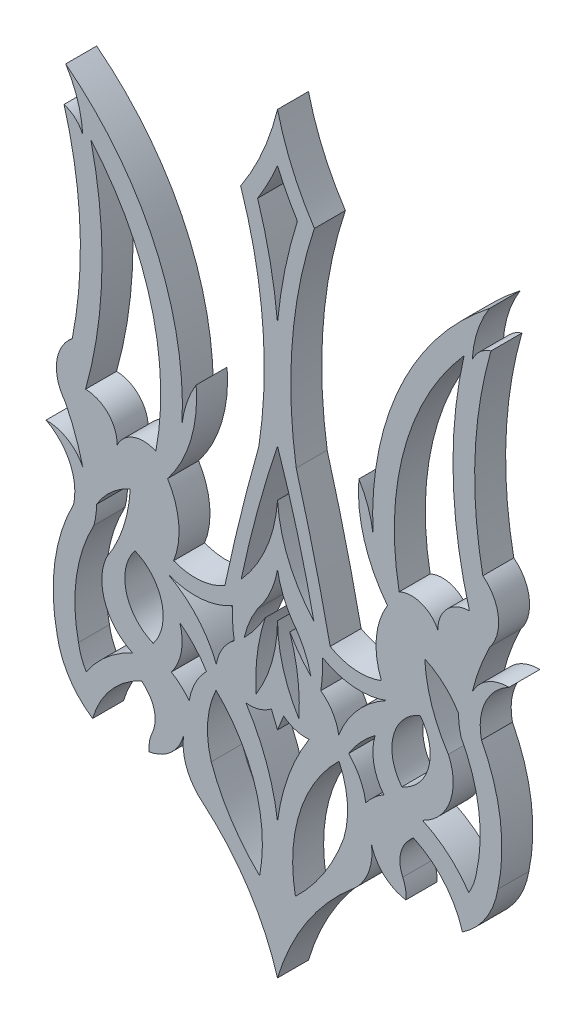
SolidWorks part; units mm, degrees
ref_plane "Спереди" through (0, 0, 0) normal (0, 0, 1) x (1, 0, 0)
ref_plane "Сверху" through (0, 0, 0) normal (0, 1, 0) x (1, 0, 0)
ref_plane "Справа" through (0, 0, 0) normal (1, 0, 0) x (0, 0, -1)
sketch "Эскиз1" [suppressed] plane through (0, 0, 0) normal (0, 0, 1) x (1, 0, 0)
  line L0 (87.6443, -23.7883) -> (87.6443, -6.8916) construction
  line L1 (87.6443, -6.8916) -> (87.6443, 352.3548) construction
  line L3 (87.6443, 68.6318) -> (85.6546, 73.5186)
  line L4 (87.6443, 68.6318) -> (89.6341, 73.5186)
  arc A0 (40.6207, 123.507) -> (44.6469, 97.5316) centre (120.5444, 122.5954) ccw
  arc A1 (40.6207, 123.507) -> (52.5559, 106.1421) centre (-51.0479, 47.7173) cw
  arc A2 (44.6469, 97.5316) -> (48.9353, 94.2011) centre (41.1464, 88.5981) cw
  arc A3 (48.9353, 94.2011) -> (48.9353, 107.9589) centre (131.9116, 101.08) cw
  arc A4 (52.5559, 106.1421) -> (53.1645, 101.095) centre (43.5258, 102.4931) cw
  arc A6 (53.1645, 101.095) -> (49.4634, 108.1691) centre (60.7326, 109.5597) cw
  arc A7 (48.935, 107.9555) -> (49.4634, 108.1691) centre (50.0675, 105.914) cw
  arc A8 (64.6822, 73.5186) -> (59.1188, 62.4923) centre (79.1678, 59.2931) ccw
  arc A9 (59.1188, 62.4923) -> (53.3348, 67.6488) centre (43.2754, 50.5432) ccw
  arc A10 (53.3348, 67.6488) -> (56.4809, 74.2644) centre (31.6379, 82.0231) ccw
  arc A11 (56.4809, 74.2644) -> (56.1084, 82.846) centre (34.8221, 77.623) ccw
  arc A12 (64.6822, 73.5186) -> (56.1084, 82.846) centre (35.8416, 55.6125) ccw
  arc A13 (41.6181, 95.7087) -> (47.5094, 72.7815) centre (35.854, 82.0071) cw
  arc A14 (41.6181, 95.7087) -> (47.5094, 72.7815) centre (53.0477, 86.4251) ccw
  arc A15 (25.6081, 56.3356) -> (38.7862, 66.0056) centre (60.8247, 22.1574) cw
  arc A16 (38.7862, 66.0056) -> (32.0434, 81.1637) centre (52.0503, 80.9846) cw
  arc A17 (40.0148, 95.7087) -> (32.0434, 81.1637) centre (52.4098, 79.4588) ccw
  arc A18 (40.0148, 95.7087) -> (34.589, 93.5264) centre (39.084, 90.1868) ccw
  arc A19 (41.6181, 98.1673) -> (34.1719, 94.2011) centre (40.4092, 91.464) ccw
  arc A20 (30.5806, 109.6374) -> (41.6181, 98.1673) centre (116.5629, 181.3309) ccw
  arc A21 (30.5806, 109.6374) -> (31.6379, 83.1978) centre (-35.2023, 93.7659) cw
  arc A22 (25.6081, 56.3356) -> (31.6379, 83.1978) centre (108.2418, 51.8945) cw
  arc A23 (34.1719, 94.2011) -> (34.589, 93.5264) centre (34.7179, 94.0723) ccw
  arc A24 (72.6436, 90.9214) -> (73.3927, 85.212) centre (115.3568, 93.6216) ccw
  arc A25 (70.0758, 80.9846) -> (73.3927, 85.212) centre (104.2196, 57.6099) cw
  arc A26 (70.0758, 80.9846) -> (60.9509, 89.3983) centre (44.0092, 61.8694) ccw
  arc A27 (60.9509, 89.3983) -> (72.6436, 90.9214) centre (64.518, 107.658) ccw
  arc A28 (80.7379, 32.2385) -> (67.7808, 69.8254) centre (31.257, 36.2081) ccw
  arc A29 (64.9288, 57.4953) -> (67.7808, 69.8254) centre (93.0087, 57.4953) cw
  arc A30 (80.7379, 32.2385) -> (64.9288, 57.4953) centre (119.8675, 74.307) cw
  arc A31 (94.5508, 32.2385) -> (110.3598, 57.4953) centre (55.4212, 74.307) ccw
  arc A32 (110.3598, 57.4953) -> (107.5079, 69.8254) centre (82.28, 57.4953) ccw
  arc A33 (94.5508, 32.2385) -> (107.5079, 69.8254) centre (144.0316, 36.2081) cw
  arc A34 (114.3378, 89.3983) -> (102.6451, 90.9214) centre (110.7707, 107.658) cw
  arc A35 (105.2129, 80.9846) -> (114.3378, 89.3983) centre (131.2795, 61.8694) cw
  arc A36 (105.2129, 80.9846) -> (101.896, 85.212) centre (71.069, 57.6099) ccw
  arc A37 (102.6451, 90.9214) -> (101.896, 85.212) centre (59.9318, 93.6216) cw
  arc A38 (141.1167, 94.2011) -> (140.6996, 93.5264) centre (140.5708, 94.0723) cw
  arc A39 (149.6806, 56.3356) -> (143.6508, 83.1978) centre (67.0469, 51.8945) ccw
  arc A40 (144.708, 109.6374) -> (143.6508, 83.1978) centre (210.491, 93.7659) ccw
  arc A41 (144.708, 109.6374) -> (133.6706, 98.1673) centre (58.7258, 181.3309) cw
  arc A42 (133.6706, 98.1673) -> (141.1167, 94.2011) centre (134.8795, 91.464) cw
  arc A43 (135.2739, 95.7087) -> (140.6996, 93.5264) centre (136.2047, 90.1868) cw
  arc A44 (135.2739, 95.7087) -> (143.2453, 81.1637) centre (122.8789, 79.4588) cw
  arc A45 (136.5025, 66.0056) -> (143.2453, 81.1637) centre (123.2384, 80.9846) ccw
  arc A46 (149.6806, 56.3356) -> (136.5025, 66.0056) centre (114.4639, 22.1574) ccw
  arc A47 (133.6706, 95.7087) -> (127.7793, 72.7815) centre (122.241, 86.4251) cw
  arc A48 (133.6706, 95.7087) -> (127.7793, 72.7815) centre (139.4347, 82.0071) ccw
  arc A49 (110.6065, 73.5186) -> (119.1803, 82.846) centre (139.4471, 55.6125) cw
  arc A50 (118.8077, 74.2644) -> (119.1803, 82.846) centre (140.4665, 77.623) cw
  arc A51 (121.9539, 67.6488) -> (118.8077, 74.2644) centre (143.6508, 82.0231) cw
  arc A52 (116.1699, 62.4923) -> (121.9539, 67.6488) centre (132.0132, 50.5432) cw
  arc A53 (110.6065, 73.5186) -> (116.1699, 62.4923) centre (96.1209, 59.2931) cw
  arc A54 (126.3537, 107.9555) -> (125.8253, 108.1691) centre (125.2211, 105.914) ccw
  arc A55 (122.1242, 101.095) -> (125.8253, 108.1691) centre (114.5561, 109.5597) ccw
  arc A56 (122.7327, 106.1421) -> (122.1242, 101.095) centre (131.7628, 102.4931) ccw
  arc A57 (126.3534, 94.2011) -> (126.3534, 107.9589) centre (43.3771, 101.08) ccw
  arc A58 (130.6418, 97.5316) -> (126.3534, 94.2011) centre (134.1423, 88.5981) ccw
  arc A59 (134.668, 123.507) -> (122.7327, 106.1421) centre (226.3366, 47.7173) ccw
  arc A60 (134.668, 123.507) -> (130.6418, 97.5316) centre (54.7443, 122.5954) cw
  arc A61 (75.9102, 104.8888) -> (87.6443, 132.8603) centre (41.1732, 135.9081) ccw
  arc A62 (75.9102, 104.8888) -> (87.6443, 148.0034) centre (451.7712, 25.7481) cw
  arc A63 (99.3785, 104.8888) -> (87.6443, 132.8603) centre (134.1154, 135.9081) cw
  arc A64 (99.3785, 104.8888) -> (87.6443, 148.0034) centre (-276.4825, 25.7481) ccw
  arc A65 (85.6546, 73.5186) -> (81.8714, 71.5335) centre (82.7705, 74.4176) cw
  arc A66 (87.6443, 53.083) -> (81.8714, 71.5335) centre (17.8027, 41.3588) ccw
  arc A67 (89.6341, 73.5186) -> (93.4173, 71.5335) centre (92.5182, 74.4176) ccw
  arc A68 (87.6443, 53.083) -> (93.4173, 71.5335) centre (157.486, 41.3588) cw
  arc A69 (87.6443, 111.5019) -> (75.9102, 93.6216) centre (57.0652, 118.7792) cw
  arc A70 (75.9102, 93.6216) -> (76.8685, 89.0118) centre (107.3806, 97.7594) ccw
  arc A71 (76.8685, 89.0118) -> (83.3447, 99.1087) centre (-45.6127, 174.6974) ccw
  arc A72 (83.3447, 99.1087) -> (78.1463, 84.8771) centre (62.4821, 98.6641) cw
  arc A73 (80.7379, 75.1856) -> (78.1463, 84.8771) centre (94.8769, 84.1588) cw
  arc A74 (80.7379, 75.1856) -> (83.7649, 75.1856) centre (82.2514, 76.6992) ccw
  arc A75 (83.7649, 75.1856) -> (82.2514, 83.8045) centre (69.0111, 77.037) ccw
  arc A76 (87.6443, 99.1626) -> (82.2514, 83.8045) centre (61.1079, 99.8548) cw
  arc A77 (91.5237, 75.1856) -> (93.0373, 83.8045) centre (106.2776, 77.037) cw
  arc A78 (94.5508, 75.1856) -> (91.5237, 75.1856) centre (93.0373, 76.6992) cw
  arc A79 (94.5508, 75.1856) -> (97.1424, 84.8771) centre (80.4118, 84.1588) ccw
  arc A80 (91.944, 99.1087) -> (97.1424, 84.8771) centre (112.8066, 98.6641) ccw
  arc A81 (98.4202, 89.0118) -> (91.944, 99.1087) centre (220.9014, 174.6974) cw
  arc A82 (99.3785, 93.6216) -> (98.4202, 89.0118) centre (67.908, 97.7594) cw
  arc A83 (87.6443, 111.5019) -> (99.3785, 93.6216) centre (118.2235, 118.7792) ccw
  arc A84 (87.6443, 99.1626) -> (93.0373, 83.8045) centre (114.1808, 99.8548) ccw
  spline S0 degree 3 poles (82.1027, 12.4657) (79.9341, 18.6914) (72.2067, 24.3569) (65.9185, 33.1059) (62.5505, 37.466) (60.1799, 39.943) (59.1555, 43.0897) (57.2647, 45.5543) (57.6286, 48.5225) (57.2368, 50.5201) (57.9183, 52.5735) (56.9495, 53.1909) (55.4861, 53.2614) (56.2486, 51.0634) (55.1896, 49.5498) (54.5036, 47.9051) (53.4075, 46.7279) (51.1035, 46.9894) (53.4402, 48.5489) (52.9045, 50.4248) (53.1315, 52.5819) (50.2686, 54.9996) (47.2077, 56.7477) (43.7411, 62.1873) (40.1307, 57.0478) (36.3563, 55.4003) (34.0123, 52.1175) (31.6232, 49.6208) (29.9193, 47.1505) (28.3136, 45.324) (28.3685, 43.599) (28.0916, 41.1132) (25.4838, 45.8805) (23.6707, 48.1541) (21.3506, 53.1893) (17.5941, 56.1294) (15.6148, 61.936) (15.5097, 68.0525) (15.9741, 74.6221) (17.289, 80.1758) (19.034, 85.376) (20.3139, 90.1381) (21.7721, 94.5747) (21.6409, 98.6721) (22.3333, 102.2806) (22.4635, 106.0403) (21.2552, 109.3896) (20.4336, 112.3281) (19.1765, 114.309) (17.3368, 115.252) (16.6151, 116.5408) (13.9501, 117.1637) (16.6597, 117.6233) (18.0151, 116.3143) (20.2861, 115.5733) (22.0029, 113.6892) (23.906, 112.8857) (24.7011, 110.1686) (25.9462, 111.2271) (24.8035, 113.2315) (24.159, 115.7716) (22.1122, 118.6068) (20.8946, 121.9867) (19.3322, 125.5441) (17.6129, 129.5089) (17.4458, 134.0046) (17.2957, 140.0912) (22.0505, 144.124) (21.6416, 148.9774) (21.7935, 153.6259) (21.4811, 159.1076) (22.6432, 165.8126) (23.1995, 173.1345) (24.6232, 181.9748) (23.765, 191.5281) (23.3918, 198.8905) (20.9362, 204.2846) (19.4503, 205.9635) (18.8575, 209.3893) (19.9586, 207.7428) (21.3919, 207.2624) (22.9247, 206.0347) (23.8774, 204.8209) (24.7322, 203.1653) (25.4143, 204.4362) (24.9731, 205.9617) (24.8711, 208.3515) (23.8043, 211.5847) (22.0026, 215.2682) (20.7759, 217.6358) (18.3336, 220.7887) (20.1657, 220.6691) (22.0637, 219.6809) (26.786, 216.3757) (31.4211, 210.9124) (35.9504, 205.2491) (38.6047, 200.7968) (41.0717, 196.8054) (43.4657, 192.4745) (45.5786, 187.3763) (48.797, 182.0166) (50.8485, 175.8116) (52.3971, 169.5049) (54.0904, 164.0713) (55.1853, 159.4561) (55.6944, 154.6896) (56.8351, 150.296) (56.4354, 145.8923) (56.5698, 142.4952) (56.7674, 140.6512) (56.6429, 138.4535) (58.4364, 140.4087) (58.5125, 143.2164) (59.7639, 147.3027) (59.1349, 150.6113) (60.546, 151.9302) (61.6062, 150.3802) (60.9783, 148.2843) (60.8195, 145.6095) (61.4206, 142.038) (60.3355, 138.7499) (59.3482, 135.2123) (57.8997, 132.2945) (56.5742, 128.4652) (54.2506, 125.5327) (53.3708, 122.086) (51.7176, 121.9147) (50.8205, 120.9474) (52.6711, 119.7166) (53.4663, 117.4305) (55.1877, 114.9802) (55.6358, 111.915) (55.4739, 109.1453) (55.6293, 106.276) (55.2189, 103.833) (54.3757, 101.9514) (54.0729, 100.4765) (53.8467, 98.7589) (56.0297, 98.8443) (57.6189, 98.1528) (59.6896, 98.0729) (61.8788, 98.0468) (64.294, 98.7043) (67.035, 98.9862) (69.132, 99.8917) (71.1395, 100.5472) (71.2883, 102.132) (71.3846, 103.98) (71.6843, 106.4326) (72.3165, 109.0602) (72.9684, 111.8403) (73.7279, 115.3959) (74.8536, 119.4926) (75.763, 123.5727) (76.9652, 127.2471) (78.2259, 131.0447) (79.3431, 135.0503) (80.7614, 142.4724) (83.4282, 150.1397) (82.9512, 158.3066) (84.0107, 163.2854) (83.59, 169.6597) (84.0559, 177.5749) (83.0482, 185.6995) (82.3476, 192.1007) (80.9886, 196.907) (79.5689, 201.5117) (78.8633, 206.1463) (77.0493, 209.8576) (76.689, 212.6324) (75.2575, 214.6117) (76.8358, 216.1245) (77.879, 218.2522) (80.4034, 220.257) (81.8163, 223.0476) (84.1194, 225.3097) (85.0477, 228.2799) (85.6117, 231.0457) (86.1825, 234.1961) (86.3896, 236.5507) (87.6443, 237.7908) knots 0 0 0 0 0.028658 0.043275 0.049534 0.054228 0.058819 0.064724 0.067657 0.072055 0.074743 0.075624 0.077091 0.080033 0.082665 0.085727 0.088171 0.089899 0.093085 0.09504 0.098738 0.10237 0.110881 0.116931 0.12534 0.130966 0.136851 0.143265 0.14693 0.150998 0.153453 0.155706 0.158836 0.169146 0.175056 0.182849 0.190745 0.202253 0.211081 0.2211 0.22852 0.236408 0.243941 0.249861 0.255135 0.260932 0.266943 0.271401 0.275062 0.277427 0.280411 0.282801 0.284651 0.288472 0.292184 0.295167 0.299832 0.302584 0.303471 0.305901 0.311305 0.31655 0.321491 0.327909 0.334558 0.341172 0.348631 0.361775 0.3653 0.370587 0.383408 0.390434 0.401952 0.417351 0.431602 0.445959 0.451733 0.457128 0.459446 0.461227 0.462918 0.467115 0.469213 0.471366 0.472356 0.474352 0.478803 0.483184 0.490226 0.496344 0.499774 0.500928 0.503188 0.510201 0.526825 0.536331 0.543637 0.550744 0.558021 0.566469 0.576206 0.586787 0.596488 0.606229 0.613083 0.618339 0.628411 0.633617 0.638971 0.643137 0.644483 0.645854 0.651354 0.659471 0.66475 0.665493 0.667175 0.670744 0.675956 0.67924 0.687368 0.691401 0.696251 0.702416 0.709709 0.714483 0.715763 0.717201 0.719145 0.723694 0.729034 0.732428 0.737794 0.741861 0.745654 0.749171 0.751124 0.753035 0.755611 0.758771 0.761604 0.764925 0.768896 0.773112 0.777417 0.779908 0.781699 0.784112 0.788713 0.792962 0.796626 0.8019 0.809759 0.816251 0.821199 0.827609 0.834746 0.840382 0.862553 0.871482 0.877812 0.8859 0.90082 0.914379 0.923643 0.930511 0.937411 0.945888 0.95211 0.95598 0.959297 0.961172 0.965011 0.970487 0.975505 0.979301 0.98517 0.98942 0.992411 1 1 1 1
  spline S1 degree 3 poles (82.1027, 12.4657) (84.2993, 11.04) (84.4898, 7.8171) (86.5127, 3.3725) (86.1614, 0.5556) (87.6443, -0.7518) knots 0 0 0 0 0.459955 0.640601 1 1 1 1
  spline S2 degree 3 poles (33.1492, 192.0361) (32.3239, 190.9776) (33.6073, 189.488) (33.8183, 187.2571) (33.5912, 184.1913) (34.768, 180.8287) (34.142, 177.3643) (34.7375, 174.2184) (33.416, 171.4352) (33.916, 167.4649) (33.6419, 163.6672) (32.426, 159.6409) (32.4019, 155.0102) (31.9063, 150.2145) (31.6211, 145.5238) (31.6773, 141.7351) (31.7172, 137.7233) (31.9002, 133.63) (32.978, 129.7883) (33.9667, 126.7415) (34.7739, 124.6373) (35.9477, 123.6027) (36.53, 122.8648) (37.5454, 121.5879) (37.4217, 123.1892) (37.5666, 124.6402) (37.3724, 126.6813) (37.8229, 128.5307) (36.0597, 129.5835) (35.484, 131.9144) (33.8251, 133.8023) (32.9988, 135.8671) (32.5775, 137.8995) (32.7484, 140.1683) (32.6969, 142.6647) (32.7204, 145.3503) (32.6794, 147.1018) (32.7472, 149.4742) (34.0356, 148.8725) (33.4484, 147.6005) (34.7834, 146.6454) (34.9602, 145.1083) (35.8397, 143.8377) (36.3762, 142.2481) (37.3299, 141.4461) (38.2688, 139.6692) (37.6169, 143.0252) (38.8152, 144.4393) (38.7035, 147.2313) (40.2653, 149.5487) (40.4515, 152.7002) (41.8549, 155.6423) (41.9859, 158.862) (43.852, 161.2171) (44.2768, 163.8863) (46.8497, 165.6494) (45.526, 168.176) (45.5393, 170.8684) (44.2898, 173.6945) (43.4083, 176.7928) (42.3605, 179.7494) (41.2587, 183.3179) (39.6884, 186.497) (37.9874, 189.0815) (37.1022, 190.9736) (35.9708, 192.4083) (35.546, 193.416) (34.9644, 194.6072) (34.481, 193.584) (35.0606, 192.9709) (35.4984, 191.9578) (36.1915, 190.5842) (37.1149, 188.6535) (38.6572, 186.6292) (39.1797, 184.1383) (40.3802, 181.9395) (40.9565, 179.5898) (41.4899, 177.0443) (41.4982, 174.3807) (41.5055, 171.851) (41.6679, 169.141) (41.2969, 167.7277) (41.5978, 165.5169) (40.8134, 166.0301) (40.5745, 166.8614) (40.5224, 168.2129) (40.2785, 170.2818) (39.5013, 172.7829) (39.3781, 175.9179) (37.6702, 178.7865) (37.4428, 182.0032) (36.3743, 184.7095) (35.2439, 187.1159) (34.7904, 189.6375) (33.4854, 190.5664) (33.1492, 192.0361) (32.3239, 190.9776) (33.6073, 189.488) knots -0.012612 -0.005761 -0.002075 0 0.007255 0.019718 0.029693 0.047672 0.065407 0.075398 0.089085 0.104151 0.127416 0.139155 0.159578 0.18822 0.203162 0.221786 0.238384 0.256378 0.275818 0.290943 0.298886 0.305592 0.309871 0.315048 0.316266 0.327773 0.336578 0.343481 0.349935 0.360303 0.374097 0.382594 0.389485 0.401439 0.412378 0.423035 0.435398 0.441227 0.444335 0.448491 0.455752 0.462248 0.468297 0.476116 0.48319 0.486816 0.495399 0.506278 0.515895 0.529177 0.542232 0.556628 0.571942 0.583258 0.594987 0.607033 0.616794 0.627412 0.64313 0.656674 0.670279 0.68463 0.706116 0.717022 0.725407 0.734132 0.739585 0.743026 0.745433 0.749878 0.753371 0.760138 0.77021 0.781747 0.793286 0.803307 0.814728 0.82514 0.837744 0.849666 0.859355 0.871506 0.875734 0.877718 0.88086 0.887378 0.895398 0.908474 0.921918 0.936196 0.951395 0.963938 0.974273 0.987388 0.994239 0.997925 1 1.007255 1.019718 1.029693 only from (32.7088, 191.4049) to (32.7088, 191.4049)
  spline S3 degree 3 poles (47.2686, 158.0754) (47.7213, 162.9241) (45.2966, 161.2742) (45.964, 159.5651) (45.3251, 157.6959) (44.4757, 155.1989) (43.5549, 151.8687) (42.7549, 147.538) (42.2447, 143.4146) (41.541, 139.9722) (41.6157, 137.7124) (41.6536, 136.1284) (41.4943, 134.633) (42.3593, 133.2272) (43.8596, 131.8548) (45.2388, 130.3901) (46.1674, 128.8242) (47.1879, 127.4737) (48.047, 126.2665) (49.7786, 126.1221) (49.3203, 127.9742) (49.5218, 129.7723) (49.5314, 132.9689) (49.4172, 136.5451) (49.5613, 140.5116) (49.4214, 144.4013) (48.898, 148.034) (48.8314, 151.5082) (48.2414, 155.3338) (47.2686, 158.0754) (47.7213, 162.9241) (45.2966, 161.2742) knots -0.143996 -0.098331 -0.035995 0 0.019516 0.041316 0.063925 0.095286 0.145724 0.199179 0.268238 0.309127 0.336564 0.356607 0.371756 0.394271 0.417403 0.452475 0.472504 0.488578 0.519641 0.527249 0.545927 0.569891 0.608527 0.666292 0.712585 0.763868 0.81928 0.856004 0.901669 0.964005 1 1.019516 1.041316 1.063925 only from (46.9629, 162.1437) to (46.9629, 162.1437)
  spline S4 degree 3 poles (128.0201, 158.0754) (127.5674, 162.9241) (129.9921, 161.2742) (129.3247, 159.5651) (129.9636, 157.6959) (130.813, 155.1989) (131.7338, 151.8687) (132.5337, 147.538) (133.044, 143.4146) (133.7477, 139.9722) (133.673, 137.7124) (133.6351, 136.1284) (133.7944, 134.633) (132.9293, 133.2272) (131.4291, 131.8548) (130.0499, 130.3901) (129.1213, 128.8242) (128.1008, 127.4737) (127.2417, 126.2665) (125.5101, 126.1221) (125.9684, 127.9742) (125.7669, 129.7723) (125.7573, 132.9689) (125.8715, 136.5451) (125.7274, 140.5116) (125.8672, 144.4013) (126.3907, 148.034) (126.4573, 151.5082) (127.0473, 155.3338) (128.0201, 158.0754) (127.5674, 162.9241) (129.9921, 161.2742) knots -0.143996 -0.098331 -0.035995 0 0.019516 0.041316 0.063925 0.095286 0.145724 0.199179 0.268238 0.309127 0.336564 0.356607 0.371756 0.394271 0.417403 0.452475 0.472504 0.488578 0.519641 0.527249 0.545927 0.569891 0.608527 0.666292 0.712585 0.763868 0.81928 0.856004 0.901669 0.964005 1 1.019516 1.041316 1.063925 only from (128.3258, 162.1437) to (128.3258, 162.1437)
  spline S5 degree 3 poles (142.1395, 192.0361) (142.9648, 190.9776) (141.6814, 189.488) (141.4704, 187.2571) (141.6974, 184.1913) (140.5207, 180.8287) (141.1466, 177.3643) (140.5512, 174.2184) (141.8727, 171.4352) (141.3727, 167.4649) (141.6467, 163.6672) (142.8627, 159.6409) (142.8867, 155.0102) (143.3824, 150.2145) (143.6676, 145.5238) (143.6114, 141.7351) (143.5715, 137.7233) (143.3884, 133.63) (142.3107, 129.7883) (141.322, 126.7415) (140.5148, 124.6373) (139.341, 123.6027) (138.7587, 122.8648) (137.7433, 121.5879) (137.867, 123.1892) (137.7221, 124.6402) (137.9163, 126.6813) (137.4658, 128.5307) (139.229, 129.5835) (139.8047, 131.9144) (141.4636, 133.8023) (142.2899, 135.8671) (142.7112, 137.8995) (142.5403, 140.1683) (142.5918, 142.6647) (142.5683, 145.3503) (142.6093, 147.1018) (142.5414, 149.4742) (141.2531, 148.8725) (141.8402, 147.6005) (140.5053, 146.6454) (140.3285, 145.1083) (139.4489, 143.8377) (138.9125, 142.2481) (137.9587, 141.4461) (137.0198, 139.6692) (137.6717, 143.0252) (136.4735, 144.4393) (136.5852, 147.2313) (135.0234, 149.5487) (134.8372, 152.7002) (133.4338, 155.6423) (133.3028, 158.862) (131.4366, 161.2171) (131.0119, 163.8863) (128.439, 165.6494) (129.7627, 168.176) (129.7494, 170.8684) (130.9989, 173.6945) (131.8804, 176.7928) (132.9282, 179.7494) (134.0299, 183.3179) (135.6003, 186.497) (137.3012, 189.0815) (138.1865, 190.9736) (139.3179, 192.4083) (139.7427, 193.416) (140.3243, 194.6072) (140.8077, 193.584) (140.2281, 192.9709) (139.7902, 191.9578) (139.0971, 190.5842) (138.1737, 188.6535) (136.6315, 186.6292) (136.109, 184.1383) (134.9085, 181.9395) (134.3322, 179.5898) (133.7988, 177.0443) (133.7905, 174.3807) (133.7832, 171.851) (133.6208, 169.141) (133.9918, 167.7277) (133.6909, 165.5169) (134.4753, 166.0301) (134.7142, 166.8614) (134.7663, 168.2129) (135.0101, 170.2818) (135.7874, 172.7829) (135.9106, 175.9179) (137.6185, 178.7865) (137.8459, 182.0032) (138.9144, 184.7095) (140.0448, 187.1159) (140.4983, 189.6375) (141.8033, 190.5664) (142.1395, 192.0361) (142.9648, 190.9776) (141.6814, 189.488) knots -0.012612 -0.005761 -0.002075 0 0.007255 0.019718 0.029693 0.047672 0.065407 0.075398 0.089085 0.104151 0.127416 0.139155 0.159578 0.18822 0.203162 0.221786 0.238384 0.256378 0.275818 0.290943 0.298886 0.305592 0.309871 0.315048 0.316266 0.327773 0.336578 0.343481 0.349935 0.360303 0.374097 0.382594 0.389485 0.401439 0.412378 0.423035 0.435398 0.441227 0.444335 0.448491 0.455752 0.462248 0.468297 0.476116 0.48319 0.486816 0.495399 0.506278 0.515895 0.529177 0.542232 0.556628 0.571942 0.583258 0.594987 0.607033 0.616794 0.627412 0.64313 0.656674 0.670279 0.68463 0.706116 0.717022 0.725407 0.734132 0.739585 0.743026 0.745433 0.749878 0.753371 0.760138 0.77021 0.781747 0.793286 0.803307 0.814728 0.82514 0.837744 0.849666 0.859355 0.871506 0.875734 0.877718 0.88086 0.887378 0.895398 0.908474 0.921918 0.936196 0.951395 0.963938 0.974273 0.987388 0.994239 0.997925 1 1.007255 1.019718 1.029693 only from (142.5799, 191.4049) to (142.5799, 191.4049)
  spline S6 degree 3 poles (93.186, 12.4657) (90.9894, 11.04) (90.7989, 7.8171) (88.776, 3.3725) (89.1273, 0.5556) (87.6443, -0.7518) knots 0 0 0 0 0.459955 0.640601 1 1 1 1
  spline S7 degree 3 poles (93.186, 12.4657) (95.3546, 18.6914) (103.082, 24.3569) (109.3702, 33.1059) (112.7382, 37.466) (115.1088, 39.943) (116.1332, 43.0897) (118.024, 45.5543) (117.6601, 48.5225) (118.0519, 50.5201) (117.3704, 52.5735) (118.3392, 53.1909) (119.8025, 53.2614) (119.0401, 51.0634) (120.0991, 49.5498) (120.7851, 47.9051) (121.8812, 46.7279) (124.1852, 46.9894) (121.8484, 48.5489) (122.3841, 50.4248) (122.1572, 52.5819) (125.02, 54.9996) (128.081, 56.7477) (131.5476, 62.1873) (135.158, 57.0478) (138.9324, 55.4003) (141.2764, 52.1175) (143.6655, 49.6208) (145.3694, 47.1505) (146.9751, 45.324) (146.9202, 43.599) (147.197, 41.1132) (149.8049, 45.8805) (151.618, 48.1541) (153.9381, 53.1893) (157.6945, 56.1294) (159.6739, 61.936) (159.779, 68.0525) (159.3146, 74.6221) (157.9997, 80.1758) (156.2547, 85.376) (154.9747, 90.1381) (153.5166, 94.5747) (153.6478, 98.6721) (152.9553, 102.2806) (152.8252, 106.0403) (154.0334, 109.3896) (154.8551, 112.3281) (156.1122, 114.309) (157.9519, 115.252) (158.6736, 116.5408) (161.3386, 117.1637) (158.629, 117.6233) (157.2736, 116.3143) (155.0026, 115.5733) (153.2858, 113.6892) (151.3827, 112.8857) (150.5876, 110.1686) (149.3425, 111.2271) (150.4852, 113.2315) (151.1297, 115.7716) (153.1765, 118.6068) (154.3941, 121.9867) (155.9564, 125.5441) (157.6757, 129.5089) (157.8429, 134.0046) (157.993, 140.0912) (153.2382, 144.124) (153.6471, 148.9774) (153.4952, 153.6259) (153.8076, 159.1076) (152.6455, 165.8126) (152.0892, 173.1345) (150.6655, 181.9748) (151.5237, 191.5281) (151.8969, 198.8905) (154.3525, 204.2846) (155.8384, 205.9635) (156.4312, 209.3893) (155.33, 207.7428) (153.8968, 207.2624) (152.364, 206.0347) (151.4112, 204.8209) (150.5565, 203.1653) (149.8744, 204.4362) (150.3156, 205.9617) (150.4175, 208.3515) (151.4844, 211.5847) (153.2861, 215.2682) (154.5127, 217.6358) (156.9551, 220.7887) (155.1229, 220.6691) (153.225, 219.6809) (148.5027, 216.3757) (143.8676, 210.9124) (139.3383, 205.2491) (136.684, 200.7968) (134.217, 196.8054) (131.823, 192.4745) (129.7101, 187.3763) (126.4917, 182.0166) (124.4402, 175.8116) (122.8915, 169.5049) (121.1983, 164.0713) (120.1034, 159.4561) (119.5943, 154.6896) (118.4535, 150.296) (118.8533, 145.8923) (118.7188, 142.4952) (118.5213, 140.6512) (118.6458, 138.4535) (116.8523, 140.4087) (116.7762, 143.2164) (115.5248, 147.3027) (116.1538, 150.6113) (114.7427, 151.9302) (113.6825, 150.3802) (114.3104, 148.2843) (114.4692, 145.6095) (113.8681, 142.038) (114.9532, 138.7499) (115.9405, 135.2123) (117.389, 132.2945) (118.7145, 128.4652) (121.0381, 125.5327) (121.9179, 122.086) (123.5711, 121.9147) (124.4682, 120.9474) (122.6176, 119.7166) (121.8223, 117.4305) (120.101, 114.9802) (119.6529, 111.915) (119.8148, 109.1453) (119.6594, 106.276) (120.0698, 103.833) (120.913, 101.9514) (121.2157, 100.4765) (121.442, 98.7589) (119.259, 98.8443) (117.6698, 98.1528) (115.5991, 98.0729) (113.4099, 98.0468) (110.9947, 98.7043) (108.2537, 98.9862) (106.1566, 99.8917) (104.1492, 100.5472) (104.0003, 102.132) (103.9041, 103.98) (103.6044, 106.4326) (102.9722, 109.0602) (102.3203, 111.8403) (101.5608, 115.3959) (100.435, 119.4926) (99.5257, 123.5727) (98.3234, 127.2471) (97.0628, 131.0447) (95.9456, 135.0503) (94.5272, 142.4724) (91.8605, 150.1397) (92.3375, 158.3066) (91.278, 163.2854) (91.6987, 169.6597) (91.2328, 177.5749) (92.2405, 185.6995) (92.9411, 192.1007) (94.3001, 196.907) (95.7197, 201.5117) (96.4254, 206.1463) (98.2393, 209.8576) (98.5997, 212.6324) (100.0312, 214.6117) (98.4528, 216.1245) (97.4097, 218.2522) (94.8853, 220.257) (93.4724, 223.0476) (91.1693, 225.3097) (90.2409, 228.2799) (89.677, 231.0457) (89.1062, 234.1961) (88.8991, 236.5507) (87.6443, 237.7908) knots 0 0 0 0 0.028658 0.043275 0.049534 0.054228 0.058819 0.064724 0.067657 0.072055 0.074743 0.075624 0.077091 0.080033 0.082665 0.085727 0.088171 0.089899 0.093085 0.09504 0.098738 0.10237 0.110881 0.116931 0.12534 0.130966 0.136851 0.143265 0.14693 0.150998 0.153453 0.155706 0.158836 0.169146 0.175056 0.182849 0.190745 0.202253 0.211081 0.2211 0.22852 0.236408 0.243941 0.249861 0.255135 0.260932 0.266943 0.271401 0.275062 0.277427 0.280411 0.282801 0.284651 0.288472 0.292184 0.295167 0.299832 0.302584 0.303471 0.305901 0.311305 0.31655 0.321491 0.327909 0.334558 0.341172 0.348631 0.361775 0.3653 0.370587 0.383408 0.390434 0.401952 0.417351 0.431602 0.445959 0.451733 0.457128 0.459446 0.461227 0.462918 0.467115 0.469213 0.471366 0.472356 0.474352 0.478803 0.483184 0.490226 0.496344 0.499774 0.500928 0.503188 0.510201 0.526825 0.536331 0.543637 0.550744 0.558021 0.566469 0.576206 0.586787 0.596488 0.606229 0.613083 0.618339 0.628411 0.633617 0.638971 0.643137 0.644483 0.645854 0.651354 0.659471 0.66475 0.665493 0.667175 0.670744 0.675956 0.67924 0.687368 0.691401 0.696251 0.702416 0.709709 0.714483 0.715763 0.717201 0.719145 0.723694 0.729034 0.732428 0.737794 0.741861 0.745654 0.749171 0.751124 0.753035 0.755611 0.758771 0.761604 0.764925 0.768896 0.773112 0.777417 0.779908 0.781699 0.784112 0.788713 0.792962 0.796626 0.8019 0.809759 0.816251 0.821199 0.827609 0.834746 0.840382 0.862553 0.871482 0.877812 0.8859 0.90082 0.914379 0.923643 0.930511 0.937411 0.945888 0.95211 0.95598 0.959297 0.961172 0.965011 0.970487 0.975505 0.979301 0.98517 0.98942 0.992411 1 1 1 1
sketch "Эскиз3" plane through (0, 0, 0) normal (0, 0, 1) x (1, 0, 0)
  line L0 (87.6443, -0.7518) -> (87.6443, -30.7439) construction
  line L1 (75.7373, 214.8271) -> (99.5514, 214.8271) construction
  line L2 (87.6443, 214.8271) -> (87.6443, 245.1652) construction
  arc A0 (75.7373, 214.8271) -> (87.6443, 242.1865) centre (3.1746, 262.6778) ccw
  arc A2 (75.7373, 214.8271) -> (81.6055, 144.874) centre (-65.9765, 167.7164) cw
  arc A3 (81.6055, 144.874) -> (70.6377, 100.4834) centre (729.5469, -38.7656) ccw
  arc A4 (70.6377, 100.4834) -> (54.1195, 99.18) centre (61.0278, 116.9518) cw
  arc A5 (54.1195, 99.18) -> (52.147, 121.1645) centre (31.2493, 108.2088) ccw
  arc A6 (52.147, 121.1645) -> (61.3729, 151.9663) centre (17.0866, 148.4485) ccw
  arc A7 (61.3729, 151.9663) -> (56.8067, 138.8308) centre (89.4398, 134.8482) ccw
  arc A8 (56.8067, 138.8308) -> (19.2332, 220.6949) centre (-40.5564, 143.6983) ccw
  arc A9 (19.2332, 220.6949) -> (24.7593, 203.6092) centre (-10.9905, 201.483) cw
  arc A10 (24.7593, 203.6092) -> (18.7084, 209.1008) centre (15.8046, 199.8218) ccw
  arc A11 (18.7084, 209.1008) -> (21.3399, 144.8893) centre (-112.1058, 171.5801) cw
  arc A12 (21.3399, 144.8893) -> (19.102, 126.0824) centre (29.6244, 134.3669) ccw
  arc A13 (19.102, 126.0824) -> (24.7805, 110.6673) centre (-47.0296, 92.9675) cw
  arc A14 (24.7805, 110.6673) -> (12.8982, 117.9136) centre (13.0914, 104.8649) ccw
  arc A15 (12.8982, 117.9136) -> (21.781, 98.7337) centre (4.7748, 102.5045) cw
  arc A16 (21.781, 98.7337) -> (16.4854, 59.6475) centre (73.3534, 71.8446) ccw
  arc A17 (16.4854, 59.6475) -> (27.9301, 41.9549) centre (42.5937, 63.9882) ccw
  arc A18 (27.9301, 41.9549) -> (43.7562, 60.4021) centre (55.9548, 33.9245) cw
  arc A19 (43.7562, 60.4021) -> (46.0707, 57.9309) centre (32.5904, 47.6247) cw
  arc A20 (47.2033, 47.6608) -> (46.2055, 41.7904) centre (57.5332, 42.885) ccw
  arc A21 (46.2055, 41.7904) -> (57.3048, 51.8905) centre (44.028, 55.3321) ccw
  arc A22 (57.3048, 51.8905) -> (63.4952, 36.2204) centre (74.3192, 49.5541) ccw
  arc A23 (63.4952, 36.2204) -> (87.6443, -0.7518) centre (13.2717, -22.957) cw
  arc A24 (111.7935, 36.2204) -> (87.6443, -0.7518) centre (162.017, -22.957) ccw
  arc A25 (117.9838, 51.8905) -> (111.7935, 36.2204) centre (100.9695, 49.5541) cw
  arc A26 (129.0831, 41.7904) -> (117.9838, 51.8905) centre (131.2607, 55.3321) cw
  arc A27 (128.0854, 47.6608) -> (129.0831, 41.7904) centre (117.7555, 42.885) cw
  arc A28 (131.5325, 60.4021) -> (129.218, 57.9309) centre (142.6983, 47.6247) ccw
  arc A29 (147.3585, 41.9549) -> (131.5325, 60.4021) centre (119.3338, 33.9245) ccw
  arc A30 (158.8033, 59.6475) -> (147.3585, 41.9549) centre (132.695, 63.9882) cw
  arc A31 (153.5077, 98.7337) -> (158.8033, 59.6475) centre (101.9353, 71.8446) cw
  arc A32 (162.3905, 117.9136) -> (153.5077, 98.7337) centre (170.5139, 102.5045) ccw
  arc A33 (150.5081, 110.6673) -> (162.3905, 117.9136) centre (162.1973, 104.8649) cw
  arc A34 (156.1867, 126.0824) -> (150.5081, 110.6673) centre (222.3183, 92.9675) ccw
  arc A35 (153.9488, 144.8893) -> (156.1867, 126.0824) centre (145.6643, 134.3669) cw
  arc A36 (156.5803, 209.1008) -> (153.9488, 144.8893) centre (287.3945, 171.5801) ccw
  arc A37 (150.5293, 203.6092) -> (156.5803, 209.1008) centre (159.4841, 199.8218) cw
  arc A38 (156.0554, 220.6949) -> (150.5293, 203.6092) centre (186.2792, 201.483) ccw
  arc A39 (118.482, 138.8308) -> (156.0554, 220.6949) centre (215.8451, 143.6983) cw
  arc A40 (113.9158, 151.9663) -> (118.482, 138.8308) centre (85.8489, 134.8482) cw
  arc A41 (123.1417, 121.1645) -> (113.9158, 151.9663) centre (158.202, 148.4485) cw
  arc A42 (121.1692, 99.18) -> (123.1417, 121.1645) centre (144.0394, 108.2088) cw
  arc A43 (104.651, 100.4834) -> (121.1692, 99.18) centre (114.2609, 116.9518) ccw
  arc A44 (93.6832, 144.874) -> (104.651, 100.4834) centre (-554.2582, -38.7656) cw
  arc A45 (99.5514, 214.8271) -> (93.6832, 144.874) centre (241.2652, 167.7164) ccw
  arc A47 (99.5514, 214.8271) -> (87.6443, 242.1865) centre (172.1141, 262.6778) cw
  arc A48 (46.0707, 57.9309) -> (47.2033, 47.6608) centre (38.1265, 51.8573) cw
  arc A49 (129.218, 57.9309) -> (128.0854, 47.6608) centre (137.1622, 51.8573) ccw
  point P110 (49.2752, 50.7157)
  point P113 (126.0135, 50.7157)
  dimension "D1" = 10
  dimension "D2" = 10
extrude "Бобышка-Вытянуть1" add sketch "Эскиз3" along normal blind 10
sketch "Эскиз4" plane through (0, 0, 0) normal (0, 0, 1) x (1, 0, 0)
  line L0 (87.6443, -0.7518) -> (87.6443, -32.3218) construction
  line L1 (85.6546, 73.5186) -> (87.6443, 68.6318)
  line L2 (87.6443, 68.6318) -> (89.6341, 73.5186)
  arc A0 (87.6443, 148.0034) -> (75.9102, 104.8888) centre (451.7712, 25.7481) ccw
  arc A1 (87.6443, 132.8603) -> (75.9102, 104.8888) centre (41.1732, 135.9081) cw
  arc A2 (67.7808, 69.8254) -> (81.8714, 24.9568) centre (33.1175, 34.2929) cw
  arc A3 (81.8714, 24.9568) -> (66.2431, 49.0031) centre (124.8767, 70.0089) cw
  arc A4 (66.2431, 49.0031) -> (67.7808, 69.8254) centre (94.1751, 57.4083) cw
  arc A5 (87.6443, 42.9742) -> (77.4425, 71.0893) centre (20.2867, 34.4413) ccw
  arc A7 (64.6822, 73.5186) -> (56.1084, 82.846) centre (35.8416, 55.6125) ccw
  arc A8 (64.6822, 73.5186) -> (59.1188, 62.4923) centre (79.1678, 59.2931) ccw
  arc A9 (53.3348, 67.6488) -> (56.1084, 82.846) centre (40.0944, 77.917) ccw
  arc A10 (59.1188, 62.4923) -> (53.3348, 67.6488) centre (43.2754, 50.5432) ccw
  arc A12 (67.908, 77.0685) -> (52.3079, 94.5198) centre (36.5563, 64.7406) ccw
  arc A13 (67.908, 77.0685) -> (73.672, 86.5781) centre (82.0844, 74.9775) cw
  arc A14 (73.672, 86.5781) -> (73.1577, 96.1649) centre (115.3568, 93.6216) cw
  arc A15 (41.6181, 95.7087) -> (47.5094, 72.7815) centre (35.854, 82.0071) cw
  arc A16 (41.6181, 95.7087) -> (47.5094, 72.7815) centre (53.0477, 86.4251) ccw
  arc A17 (87.6443, 113.4827) -> (81.1136, 99.1626) centre (57.0652, 118.7792) cw
  arc A18 (81.1136, 99.1626) -> (76.8685, 89.0118) centre (107.8316, 82.0261) ccw
  arc A19 (76.8685, 89.0118) -> (83.6747, 98.0262) centre (42.0362, 122.3882) ccw
  arc A20 (83.6747, 98.0262) -> (80.7379, 75.1856) centre (141.0886, 79.0348) ccw
  arc A21 (80.7379, 75.1856) -> (87.6443, 99.1626) centre (41.3033, 99.5278) ccw
  arc A22 (94.5508, 75.1856) -> (87.6443, 99.1626) centre (133.9853, 99.5278) cw
  arc A23 (91.614, 98.0262) -> (94.5508, 75.1856) centre (34.2001, 79.0348) cw
  arc A24 (98.4202, 89.0118) -> (91.614, 98.0262) centre (133.2525, 122.3882) cw
  arc A25 (94.1751, 99.1626) -> (98.4202, 89.0118) centre (67.4571, 82.0261) cw
  arc A26 (87.6443, 113.4827) -> (94.1751, 99.1626) centre (118.2235, 118.7792) ccw
  arc A27 (133.6706, 95.7087) -> (127.7793, 72.7815) centre (122.241, 86.4251) cw
  arc A28 (133.6706, 95.7087) -> (127.7793, 72.7815) centre (139.4347, 82.0071) ccw
  arc A29 (101.6166, 86.5781) -> (102.131, 96.1649) centre (59.9318, 93.6216) ccw
  arc A30 (107.3806, 77.0685) -> (101.6166, 86.5781) centre (93.2043, 74.9775) ccw
  arc A31 (107.3806, 77.0685) -> (122.9808, 94.5198) centre (138.7324, 64.7406) cw
  arc A33 (116.1699, 62.4923) -> (121.9539, 67.6488) centre (132.0132, 50.5432) cw
  arc A34 (121.9539, 67.6488) -> (119.1803, 82.846) centre (135.1943, 77.917) cw
  arc A35 (110.6065, 73.5186) -> (116.1699, 62.4923) centre (96.1209, 59.2931) cw
  arc A36 (110.6065, 73.5186) -> (119.1803, 82.846) centre (139.4471, 55.6125) cw
  arc A38 (87.6443, 42.9742) -> (97.8462, 71.0893) centre (155.002, 34.4413) cw
  arc A39 (109.0456, 49.0031) -> (107.5079, 69.8254) centre (81.1136, 57.4083) ccw
  arc A40 (93.4173, 24.9568) -> (109.0456, 49.0031) centre (50.412, 70.0089) ccw
  arc A41 (107.5079, 69.8254) -> (93.4173, 24.9568) centre (142.1712, 34.2929) ccw
  arc A42 (87.6443, 132.8603) -> (99.3785, 104.8888) centre (134.1154, 135.9081) ccw
  arc A43 (87.6443, 148.0034) -> (99.3785, 104.8888) centre (-276.4825, 25.7481) cw
  arc A44 (77.4425, 71.0893) -> (85.6546, 73.5186) centre (78.6188, 82.2081) ccw
  arc A45 (97.8462, 71.0893) -> (89.6341, 73.5186) centre (96.6699, 82.2081) cw
  arc A71 (40.8271, 66.7598) -> (32.4731, 89.3983) centre (47.9693, 82.256) cw
  arc A72 (32.4731, 89.3983) -> (40.0944, 112.2971) centre (-5.435, 114.7328) ccw
  arc A73 (40.0944, 112.2971) -> (29.194, 102.5045) centre (50.3212, 89.9502) ccw
  arc A75 (28.3709, 96.2178) -> (16.1626, 124.1058) centre (4.7748, 102.5045) ccw
  arc A76 (23.3657, 60.9491) -> (25.8866, 53.997) centre (42.5937, 63.9882) ccw
  arc A77 (28.3709, 96.2178) -> (23.3657, 60.9491) centre (73.3534, 71.8446) ccw
  arc A78 (40.8271, 66.7598) -> (25.8866, 53.997) centre (55.9548, 33.9245) ccw
  arc A79 (28.3709, 96.2178) -> (29.194, 102.5045) centre (4.7748, 102.5045) ccw
  arc A80 (23.3657, 60.9491) -> (25.8866, 53.997) centre (42.5937, 63.9882) ccw
  arc A81 (28.3709, 96.2178) -> (23.3657, 60.9491) centre (73.3534, 71.8446) ccw
  arc A82 (40.8271, 66.7598) -> (25.8866, 53.997) centre (55.9548, 33.9245) ccw
  arc A266 (49.8154, 139.1803) -> (14.94, 215.166) centre (-40.5564, 143.6983) ccw
  arc A267 (48.3554, 126.9004) -> (27.3869, 203.4577) centre (-40.5564, 143.6983) ccw
  arc A268 (25.6623, 132.9232) -> (35.854, 122.3882) centre (25.4906, 122.5599) cw
  arc A269 (28.204, 143.5164) -> (25.4371, 211.0307) centre (-112.1058, 171.5801) ccw
  arc A270 (25.6623, 132.9232) -> (27.3869, 203.4577) centre (-112.1058, 171.5801) ccw
  arc A271 (35.854, 122.3882) -> (48.3554, 126.9004) centre (44.3608, 118.3936) cw
  arc A272 (151.923, 60.9491) -> (149.4021, 53.997) centre (132.695, 63.9882) cw
  arc A273 (134.4616, 66.7598) -> (149.4021, 53.997) centre (119.3338, 33.9245) cw
  arc A274 (134.4616, 66.7598) -> (142.8156, 89.3983) centre (127.3193, 82.256) ccw
  arc A275 (146.9178, 96.2178) -> (151.923, 60.9491) centre (101.9353, 71.8446) cw
  arc A276 (146.9178, 96.2178) -> (146.0947, 102.5045) centre (170.5139, 102.5045) cw
  arc A277 (135.1943, 112.2971) -> (146.0947, 102.5045) centre (124.9674, 89.9502) cw
  arc A278 (142.8156, 89.3983) -> (135.1943, 112.2971) centre (180.7237, 114.7328) cw
  arc A279 (139.4347, 122.3882) -> (126.9333, 126.9004) centre (130.9279, 118.3936) ccw
  arc A280 (149.6264, 132.9232) -> (139.4347, 122.3882) centre (149.798, 122.5599) ccw
  arc A281 (149.6264, 132.9232) -> (147.9018, 203.4577) centre (287.3945, 171.5801) cw
  arc A282 (126.9333, 126.9004) -> (147.9018, 203.4577) centre (215.8451, 143.6983) cw
  arc A322 (94.0669, 214.1199) -> (88.742, 144.1093) centre (241.2652, 167.7164) ccw
  arc A323 (82.7853, 241.0077) -> (94.0669, 214.1199) centre (172.1141, 262.6778) ccw
  arc A324 (94.0669, 214.1199) -> (87.6443, 182.5908) centre (241.2652, 167.7164) ccw
  arc A325 (87.6443, 226.4274) -> (94.0669, 214.1199) centre (172.1141, 262.6778) ccw
  arc A328 (122.9808, 94.5198) -> (102.131, 96.1649) centre (114.2609, 116.9518) cw
  arc A329 (86.5466, 144.1093) -> (81.2218, 214.1199) centre (-65.9765, 167.7164) ccw
  arc A330 (81.2218, 214.1199) -> (92.5034, 241.0077) centre (3.1746, 262.6778) ccw
  arc A331 (87.6443, 182.5908) -> (81.2218, 214.1199) centre (-65.9765, 167.7164) ccw
  arc A332 (81.2218, 214.1199) -> (87.6443, 226.4274) centre (3.1746, 262.6778) ccw
  arc A333 (52.3079, 94.5198) -> (73.1577, 96.1649) centre (61.0278, 116.9518) ccw
  arc A334 (52.3079, 94.5198) -> (73.1577, 96.1649) centre (61.0278, 116.9518) ccw
  dimension "D1" = 7
  dimension "D2" = 7
  dimension "D3" = 7
  dimension "D4" = 5
  dimension "D5" = 5
  dimension "D6" = 5
extrude "Вырез-Вытянуть4" cut sketch "Эскиз4" along normal blind 10
